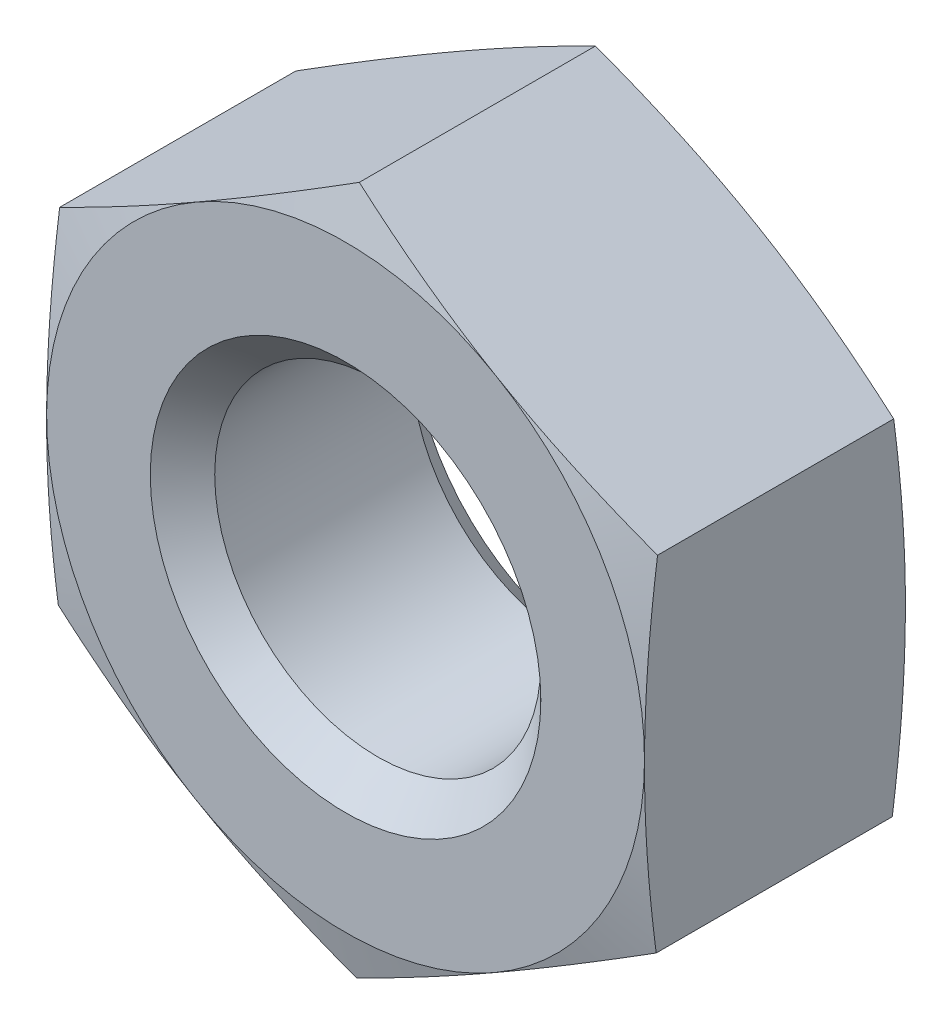
SolidWorks part; units mm, degrees
extrude "基体-拉伸" add sketch "草图1" along normal blind 2.4
sketch "草图1" plane through (0, 0, 0) normal (0, 0, 1) x (1, 0, 0)
  line L0 (-26.8088, 0) -> (37.1748, 0) construction
  line L1 (0, 25.0215) -> (0, -25.0215) construction
  line L3 (0.0125, 3.1754) -> (-2.7437, 1.5985)
  line L4 (-2.7437, 1.5985) -> (-2.7562, -1.5769)
  line L5 (-2.7562, -1.5769) -> (-0.0125, -3.1754)
  line L6 (-0.0125, -3.1754) -> (2.7437, -1.5985)
  line L7 (2.7437, -1.5985) -> (2.7562, 1.5769)
  line L8 (2.7562, 1.5769) -> (0.0125, 3.1754)
  circle A0 centre (0, 0) radius 2.75 construction
  circle A1 centre (0, 0) radius 1.5
  dimension "D" = 3
  dimension "D1" = 5.5
  dimension "D2" = 6.3508
cosmetic thread "装饰螺纹线1"
chamfer "倒角1" distance 0.2964 angle 45 2 edges at (1.5, 0, 0) (1.5, 0, 2.4)
ref_plane "基准面1" through (0, 0, 0) normal (0, 0, 1) x (1, 0, 0)
ref_plane "基准面2" through (0, 0, 0) normal (0, 1, 0) x (1, 0, 0)
ref_plane "基准面3" through (0, 0, 0) normal (1, 0, 0) x (0, 0, -1)
sketch "尺寸草图" plane through (0, 0, 0) normal (0, 0, 1) x (1, 0, 0)
  line L0 (0, 0) -> (33.9749, 0)
  line L1 (33.9749, 0) -> (37.4249, 0)
  line L2 (37.4249, 0) -> (42.0249, 0)
  line L3 (-2.8571, 0) -> (0, 0)
  point P3 (3, 0)
  point P4 (1.5, 0)
  point P5 (6.01, 0)
  point P6 (2.4, 0)
  point P7 (6.4, 0)
  point P8 (5.5, 0)
  dimension "D" = 3
  dimension "P" = 1.5
  dimension "e" = 6.01
  dimension "m" = 2.4
  dimension "mw" = 6.4
  dimension "s" = 5.5
  dimension "da" = 3.45
  dimension "dw" = 4.6
  dimension "D1" = 2.8571
sketch "草图2" plane through (0, 0, 0) normal (0, 0, -1) x (-1, 0, 0)
  circle A0 centre (0, 0) radius 2.75
  circle A1 centre (0, 0) radius 1.5 construction
  dimension "s" = 5.5
extrude "切除-拉伸1" cut sketch "草图2" against normal through all draft 75 flip side to cut
sketch "草图3" plane through (0, 0, 2.4) normal (0, 0, 1) x (1, 0, 0)
  circle A0 centre (0, 0) radius 2.75
  dimension "D1" = 5.5
extrude "切除-拉伸2" cut sketch "草图3" against normal through all draft 75 flip side to cut
equation "\"D1@尺寸草图\" = \"D@尺寸草图\" / 1.05"
equation "\"D@草图1\" = \"D@尺寸草图\""
equation "\"m@基体-拉伸\" = \"m@尺寸草图\""
equation "\"D1@草图3\" = \"s@尺寸草图\""
equation "\"s@草图2\" = \"s@尺寸草图\""
equation "\"D2@装饰螺纹线1\" =\"D@尺寸草图\""
equation "\"D1@倒角1\" =  ( \"da@尺寸草图\" - \"D1@尺寸草图\" )  / 2"
